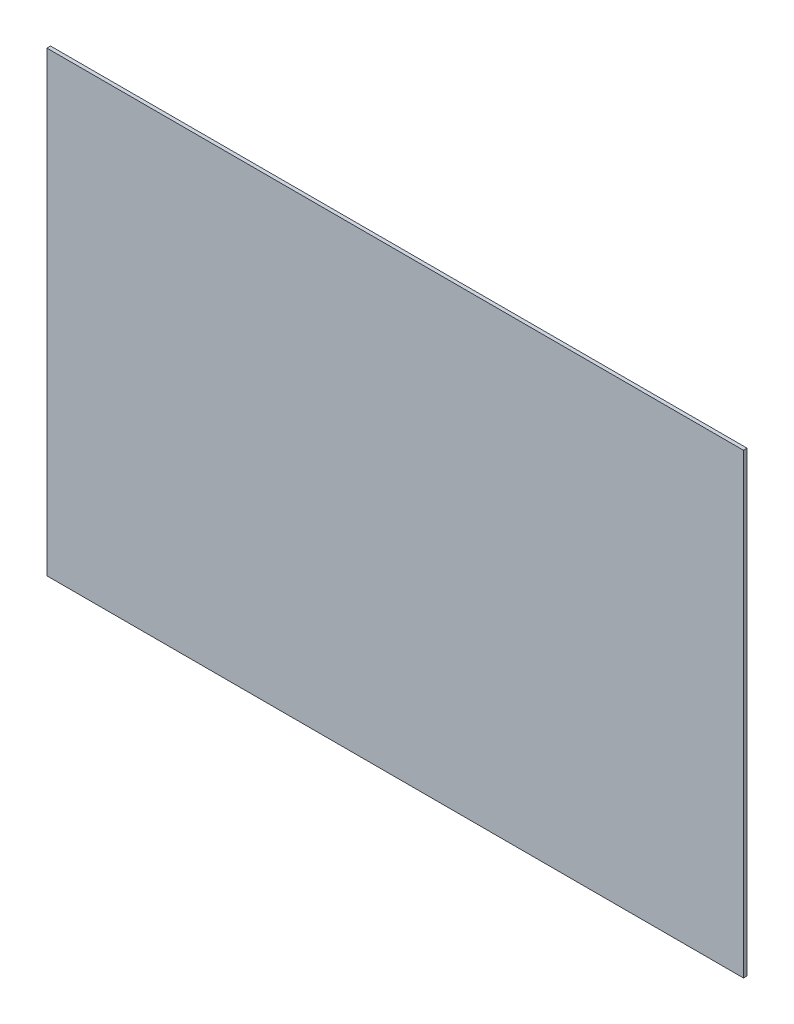
SolidWorks part; units mm, degrees
ref_plane "Front Plane" through (0, 0, 0) normal (0, 0, 1) x (1, 0, 0)
ref_plane "Top Plane" through (0, 0, 0) normal (0, 1, 0) x (1, 0, 0)
ref_plane "Right Plane" through (0, 0, 0) normal (1, 0, 0) x (0, 0, -1)
sketch "Sketch1" plane through (0, 0, 0) normal (0, 0, 1) x (1, 0, 0)
  line L1 (0, 0) -> (1219.2, 0)
  line L2 (0, 0) -> (0, 800)
  line L4 (1219.2, 0) -> (1219.2, 800)
  line L10 (0, 800) -> (1219.2, 800)
  dimension "D1" = 1219.2
  dimension "D2" = 800
extrude "Boss-Extrude1" add sketch "Sketch1" along normal blind 6.35 contours L4 L10 L2 L1
